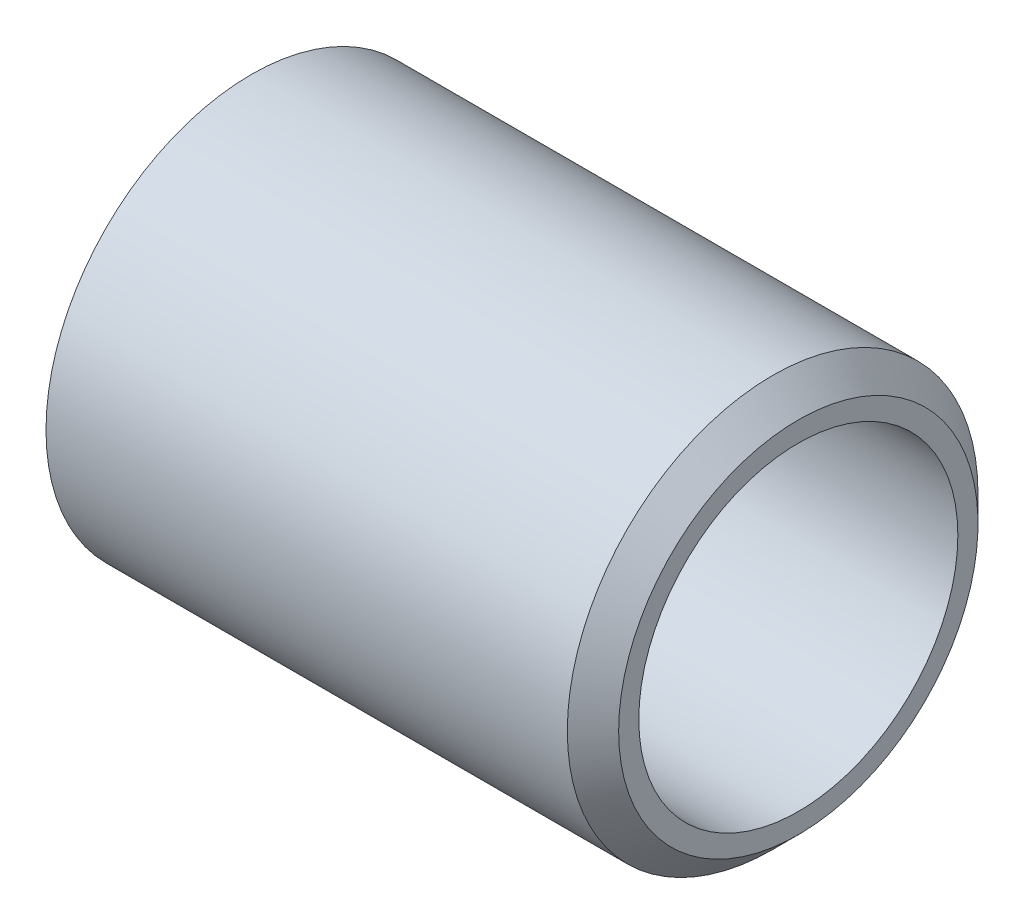
SolidWorks part; units mm, degrees
ref_plane "Plane1" through (0, 0, 0) normal (0, 0, 1) x (1, 0, 0)
ref_plane "Plane2" through (0, 0, 0) normal (0, 1, 0) x (1, 0, 0)
ref_plane "Plane3" through (0, 0, 0) normal (1, 0, 0) x (0, 0, -1)
sketch "Sketch1" plane through (0, 0, 0) normal (0, 0, 1) x (1, 0, 0)
  line L0 (0, 0) -> (76.2, 0) construction
  line L1 (0, 24.6126) -> (0, 28.6068)
  line L4 (0, 28.6068) -> (72.6242, 28.6068)
  line L5 (72.6242, 28.6068) -> (76.2, 25.0309)
  line L6 (76.2, 25.0309) -> (76.2, 22.225)
  line L7 (76.2, 22.225) -> (2.3876, 22.225)
  line L8 (72.6242, -28.6068) -> (76.2, -25.0309) construction
  line L9 (76.2, -22.225) -> (0, -22.225) construction
  line L10 (0, -28.6068) -> (72.6242, -28.6068) construction
  arc A1 (0, 24.6126) -> (2.3876, 22.225) centre (2.3876, 24.6126) ccw
  point P20 (0, 22.225)
  dimension "Head_radius" = 2.3876
  dimension "Hole_dia" = 44.45
  dimension "Body_dia" = 57.2135
  dimension "Body_len" = 76.2
  dimension "D1" = 50.0618
  dimension "D2" = 45
revolve "BaseBody" add sketch "Sketch1" angle 360 about L0
equation "\"D1@Sketch1\" = \"Body_dia@Sketch1\" * .875"
